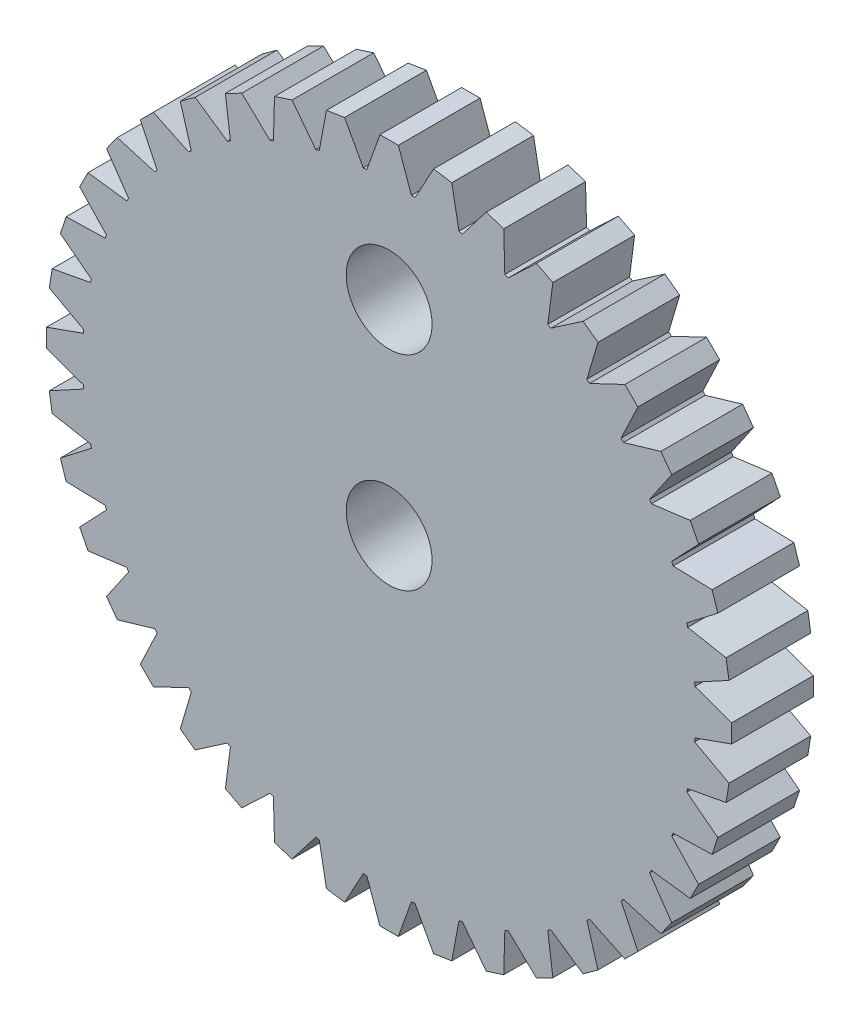
SolidWorks part; units mm, degrees
ref_plane "Front Plane" through (0, 0, 0) normal (0, 0, 1) x (1, 0, 0)
ref_plane "Top Plane" through (0, 0, 0) normal (0, 1, 0) x (1, 0, 0)
ref_plane "Right Plane" through (0, 0, 0) normal (1, 0, 0) x (0, 0, -1)
sketch "Sketch7" plane through (0, 0, 0) normal (0, 0, 1) x (1, 0, 0)
  line L0 (0, 8.9657) -> (0, 8.3802) construction
  line L1 (-0.225, 8.3802) -> (0.225, 8.3802)
  line L2 (0.225, 8.3802) -> (0.545, 7.4802)
  line L3 (-0.225, 8.3802) -> (-0.545, 7.4802)
  line L4 (1.0887, 8.3122) -> (0.6319, 7.4733)
  line L5 (1.0887, 8.3122) -> (1.5332, 8.2418)
  line L6 (1.5332, 8.2418) -> (1.7084, 7.3028)
  line L7 (2.3756, 8.0395) -> (1.7932, 7.2825)
  line L8 (2.3756, 8.0395) -> (2.8036, 7.9005)
  line L9 (2.8036, 7.9005) -> (2.8298, 6.9457)
  line L10 (3.604, 7.5689) -> (2.9103, 6.9123)
  line L11 (3.604, 7.5689) -> (4.005, 7.3646)
  line L12 (4.005, 7.3646) -> (3.8815, 6.4175)
  line L13 (4.7437, 6.912) -> (3.9558, 6.3719)
  line L14 (4.7437, 6.912) -> (5.1078, 6.6474)
  line L15 (5.1078, 6.6474) -> (4.8376, 5.7312)
  line L16 (5.7666, 6.0848) -> (4.9039, 5.6747)
  line L17 (5.7666, 6.0848) -> (6.0848, 5.7666)
  line L18 (6.0848, 5.7666) -> (5.6747, 4.9039)
  line L19 (6.6474, 5.1078) -> (5.7312, 4.8376)
  line L20 (6.6474, 5.1078) -> (6.912, 4.7437)
  line L21 (6.912, 4.7437) -> (6.3719, 3.9558)
  line L22 (7.3646, 4.005) -> (6.4175, 3.8815)
  line L23 (7.3646, 4.005) -> (7.5689, 3.604)
  line L24 (7.5689, 3.604) -> (6.9123, 2.9103)
  line L25 (7.9005, 2.8036) -> (6.9457, 2.8298)
  line L26 (7.9005, 2.8036) -> (8.0395, 2.3756)
  line L27 (8.0395, 2.3756) -> (7.2825, 1.7932)
  line L28 (8.2418, 1.5332) -> (7.3028, 1.7084)
  line L29 (8.2418, 1.5332) -> (8.3122, 1.0887)
  line L30 (8.3122, 1.0887) -> (7.4733, 0.6319)
  line L31 (8.3802, 0.225) -> (7.4802, 0.545)
  line L32 (8.3802, 0.225) -> (8.3802, -0.225)
  line L33 (8.3802, -0.225) -> (7.4802, -0.545)
  line L34 (8.3122, -1.0887) -> (7.4733, -0.6319)
  line L35 (8.3122, -1.0887) -> (8.2418, -1.5332)
  line L36 (8.2418, -1.5332) -> (7.3028, -1.7084)
  line L37 (8.0395, -2.3756) -> (7.2825, -1.7932)
  line L38 (8.0395, -2.3756) -> (7.9005, -2.8036)
  line L39 (7.9005, -2.8036) -> (6.9457, -2.8298)
  line L40 (7.5689, -3.604) -> (6.9123, -2.9103)
  line L41 (7.5689, -3.604) -> (7.3646, -4.005)
  line L42 (7.3646, -4.005) -> (6.4175, -3.8815)
  line L43 (6.912, -4.7437) -> (6.3719, -3.9558)
  line L44 (6.912, -4.7437) -> (6.6474, -5.1078)
  line L45 (6.6474, -5.1078) -> (5.7312, -4.8376)
  line L46 (6.0848, -5.7666) -> (5.6747, -4.9039)
  line L47 (6.0848, -5.7666) -> (5.7666, -6.0848)
  line L48 (5.7666, -6.0848) -> (4.9039, -5.6747)
  line L49 (5.1078, -6.6474) -> (4.8376, -5.7312)
  line L50 (5.1078, -6.6474) -> (4.7437, -6.912)
  line L51 (4.7437, -6.912) -> (3.9558, -6.3719)
  line L52 (4.005, -7.3646) -> (3.8815, -6.4175)
  line L53 (4.005, -7.3646) -> (3.604, -7.5689)
  line L54 (3.604, -7.5689) -> (2.9103, -6.9123)
  line L55 (2.8036, -7.9005) -> (2.8298, -6.9457)
  line L56 (2.8036, -7.9005) -> (2.3756, -8.0395)
  line L57 (2.3756, -8.0395) -> (1.7932, -7.2825)
  line L58 (1.5332, -8.2418) -> (1.7084, -7.3028)
  line L59 (1.5332, -8.2418) -> (1.0887, -8.3122)
  line L60 (1.0887, -8.3122) -> (0.6319, -7.4733)
  line L61 (0.225, -8.3802) -> (0.545, -7.4802)
  line L62 (0.225, -8.3802) -> (-0.225, -8.3802)
  line L63 (-0.225, -8.3802) -> (-0.545, -7.4802)
  line L64 (-1.0887, -8.3122) -> (-0.6319, -7.4733)
  line L65 (-1.0887, -8.3122) -> (-1.5332, -8.2418)
  line L66 (-1.5332, -8.2418) -> (-1.7084, -7.3028)
  line L67 (-2.3756, -8.0395) -> (-1.7932, -7.2825)
  line L68 (-2.3756, -8.0395) -> (-2.8036, -7.9005)
  line L69 (-2.8036, -7.9005) -> (-2.8298, -6.9457)
  line L70 (-3.604, -7.5689) -> (-2.9103, -6.9123)
  line L71 (-3.604, -7.5689) -> (-4.005, -7.3646)
  line L72 (-4.005, -7.3646) -> (-3.8815, -6.4175)
  line L73 (-4.7437, -6.912) -> (-3.9558, -6.3719)
  line L74 (-4.7437, -6.912) -> (-5.1078, -6.6474)
  line L75 (-5.1078, -6.6474) -> (-4.8376, -5.7312)
  line L76 (-5.7666, -6.0848) -> (-4.9039, -5.6747)
  line L77 (-5.7666, -6.0848) -> (-6.0848, -5.7666)
  line L78 (-6.0848, -5.7666) -> (-5.6747, -4.9039)
  line L79 (-6.6474, -5.1078) -> (-5.7312, -4.8376)
  line L80 (-6.6474, -5.1078) -> (-6.912, -4.7437)
  line L81 (-6.912, -4.7437) -> (-6.3719, -3.9558)
  line L82 (-7.3646, -4.005) -> (-6.4175, -3.8815)
  line L83 (-7.3646, -4.005) -> (-7.5689, -3.604)
  line L84 (-7.5689, -3.604) -> (-6.9123, -2.9103)
  line L85 (-7.9005, -2.8036) -> (-6.9457, -2.8298)
  line L86 (-7.9005, -2.8036) -> (-8.0395, -2.3756)
  line L87 (-8.0395, -2.3756) -> (-7.2825, -1.7932)
  line L88 (-8.2418, -1.5332) -> (-7.3028, -1.7084)
  line L89 (-8.2418, -1.5332) -> (-8.3122, -1.0887)
  line L90 (-8.3122, -1.0887) -> (-7.4733, -0.6319)
  line L91 (-8.3802, -0.225) -> (-7.4802, -0.545)
  line L92 (-8.3802, -0.225) -> (-8.3802, 0.225)
  line L93 (-8.3802, 0.225) -> (-7.4802, 0.545)
  line L94 (-8.3122, 1.0887) -> (-7.4733, 0.6319)
  line L95 (-8.3122, 1.0887) -> (-8.2418, 1.5332)
  line L96 (-8.2418, 1.5332) -> (-7.3028, 1.7084)
  line L97 (-8.0395, 2.3756) -> (-7.2825, 1.7932)
  line L98 (-8.0395, 2.3756) -> (-7.9005, 2.8036)
  line L99 (-7.9005, 2.8036) -> (-6.9457, 2.8298)
  line L100 (-7.5689, 3.604) -> (-6.9123, 2.9103)
  line L101 (-7.5689, 3.604) -> (-7.3646, 4.005)
  line L102 (-7.3646, 4.005) -> (-6.4175, 3.8815)
  line L103 (-6.912, 4.7437) -> (-6.3719, 3.9558)
  line L104 (-6.912, 4.7437) -> (-6.6474, 5.1078)
  line L105 (-6.6474, 5.1078) -> (-5.7312, 4.8376)
  line L106 (-6.0848, 5.7666) -> (-5.6747, 4.9039)
  line L107 (-6.0848, 5.7666) -> (-5.7666, 6.0848)
  line L108 (-5.7666, 6.0848) -> (-4.9039, 5.6747)
  line L109 (-5.1078, 6.6474) -> (-4.8376, 5.7312)
  line L110 (-5.1078, 6.6474) -> (-4.7437, 6.912)
  line L111 (-4.7437, 6.912) -> (-3.9558, 6.3719)
  line L112 (-4.005, 7.3646) -> (-3.8815, 6.4175)
  line L113 (-4.005, 7.3646) -> (-3.604, 7.5689)
  line L114 (-3.604, 7.5689) -> (-2.9103, 6.9123)
  line L115 (-2.8036, 7.9005) -> (-2.8298, 6.9457)
  line L116 (-2.8036, 7.9005) -> (-2.3756, 8.0395)
  line L117 (-2.3756, 8.0395) -> (-1.7932, 7.2825)
  line L118 (-1.5332, 8.2418) -> (-1.7084, 7.3028)
  line L119 (-1.5332, 8.2418) -> (-1.0887, 8.3122)
  line L120 (-1.0887, 8.3122) -> (-0.6319, 7.4733)
  line L121 (0, -8.3802) -> (0, -9.5812) construction
  arc A0 (-6.3719, 3.9558) -> (-6.4175, 3.8815) centre (0, 0) ccw
  arc A1 (-5.6747, 4.9039) -> (-5.7312, 4.8376) centre (0, 0) ccw
  arc A2 (-4.8376, 5.7312) -> (-4.9039, 5.6747) centre (0, 0) ccw
  arc A3 (-3.8815, 6.4175) -> (-3.9558, 6.3719) centre (0, 0) ccw
  arc A4 (-2.8298, 6.9457) -> (-2.9103, 6.9123) centre (0, 0) ccw
  arc A5 (-1.7084, 7.3028) -> (-1.7932, 7.2825) centre (0, 0) ccw
  arc A6 (-0.545, 7.4802) -> (-0.6319, 7.4733) centre (0, 0) ccw
  arc A7 (0.6319, 7.4733) -> (0.545, 7.4802) centre (0, 0) ccw
  arc A8 (1.7932, 7.2825) -> (1.7084, 7.3028) centre (0, 0) ccw
  arc A9 (2.9103, 6.9123) -> (2.8298, 6.9457) centre (0, 0) ccw
  arc A10 (3.9558, 6.3719) -> (3.8815, 6.4175) centre (0, 0) ccw
  arc A11 (-1.7932, -7.2825) -> (-1.7084, -7.3028) centre (0, 0) ccw
  arc A12 (-0.6319, -7.4733) -> (-0.545, -7.4802) centre (0, 0) ccw
  arc A13 (0.545, -7.4802) -> (0.6319, -7.4733) centre (0, 0) ccw
  arc A14 (1.7084, -7.3028) -> (1.7932, -7.2825) centre (0, 0) ccw
  arc A15 (2.8298, -6.9457) -> (2.9103, -6.9123) centre (0, 0) ccw
  arc A16 (3.8815, -6.4175) -> (3.9558, -6.3719) centre (0, 0) ccw
  arc A17 (4.8376, -5.7312) -> (4.9039, -5.6747) centre (0, 0) ccw
  arc A18 (5.6747, -4.9039) -> (5.7312, -4.8376) centre (0, 0) ccw
  arc A19 (6.3719, -3.9558) -> (6.4175, -3.8815) centre (0, 0) ccw
  arc A20 (6.9123, -2.9103) -> (6.9457, -2.8298) centre (0, 0) ccw
  arc A21 (7.2825, -1.7932) -> (7.3028, -1.7084) centre (0, 0) ccw
  arc A22 (7.4733, -0.6319) -> (7.4802, -0.545) centre (0, 0) ccw
  arc A23 (7.4802, 0.545) -> (7.4733, 0.6319) centre (0, 0) ccw
  arc A24 (7.3028, 1.7084) -> (7.2825, 1.7932) centre (0, 0) ccw
  arc A25 (4.9039, 5.6747) -> (4.8376, 5.7312) centre (0, 0) ccw
  arc A26 (5.7312, 4.8376) -> (5.6747, 4.9039) centre (0, 0) ccw
  arc A27 (6.4175, 3.8815) -> (6.3719, 3.9558) centre (0, 0) ccw
  arc A28 (6.9457, 2.8298) -> (6.9123, 2.9103) centre (0, 0) ccw
  arc A29 (-7.2825, 1.7932) -> (-7.3028, 1.7084) centre (0, 0) ccw
  arc A30 (-6.9123, 2.9103) -> (-6.9457, 2.8298) centre (0, 0) ccw
  arc A31 (-7.4733, 0.6319) -> (-7.4802, 0.545) centre (0, 0) ccw
  arc A32 (-7.4802, -0.545) -> (-7.4733, -0.6319) centre (0, 0) ccw
  arc A33 (-6.9457, -2.8298) -> (-6.9123, -2.9103) centre (0, 0) ccw
  arc A34 (-7.3028, -1.7084) -> (-7.2825, -1.7932) centre (0, 0) ccw
  arc A35 (-6.4175, -3.8815) -> (-6.3719, -3.9558) centre (0, 0) ccw
  arc A36 (-5.7312, -4.8376) -> (-5.6747, -4.9039) centre (0, 0) ccw
  arc A37 (-4.9039, -5.6747) -> (-4.8376, -5.7312) centre (0, 0) ccw
  arc A38 (-3.9558, -6.3719) -> (-3.8815, -6.4175) centre (0, 0) ccw
  arc A39 (-2.9103, -6.9123) -> (-2.8298, -6.9457) centre (0, 0) ccw
  point P9 (0, 8.3802)
  point P169 (0, 0)
  dimension "D1" = 15
  dimension "D2" = 0.45
  dimension "D3" = 0.9
  dimension "D4" = 0.32
extrude "Boss-Extrude5" add sketch "Sketch7" along normal blind 2
sketch "Sketch8" plane through (0, 0, 2) normal (0, 0, 1) x (1, 0, 0)
  line L0 (0, 0) -> (0, 5) construction
  line L1 (-2.5, 0) -> (-2.5, 5)
  line L2 (2.5, 0) -> (2.5, 5)
  arc A0 (-2.5, 0) -> (2.5, 0) centre (0, 0) ccw
  arc A1 (2.5, 5) -> (-2.5, 5) centre (0, 5) ccw
  circle A2 centre (0, 5) radius 1.05
  circle A3 centre (0, 0) radius 1.05
  point P3 (0, 2.5)
  dimension "D2" = 2.5
  dimension "D3" = 2.1
  dimension "D4" = 2.1
  dimension "D1" = 5
extrude "Cut-Extrude2" cut sketch "Sketch8" against normal through all contours A2 | A3
